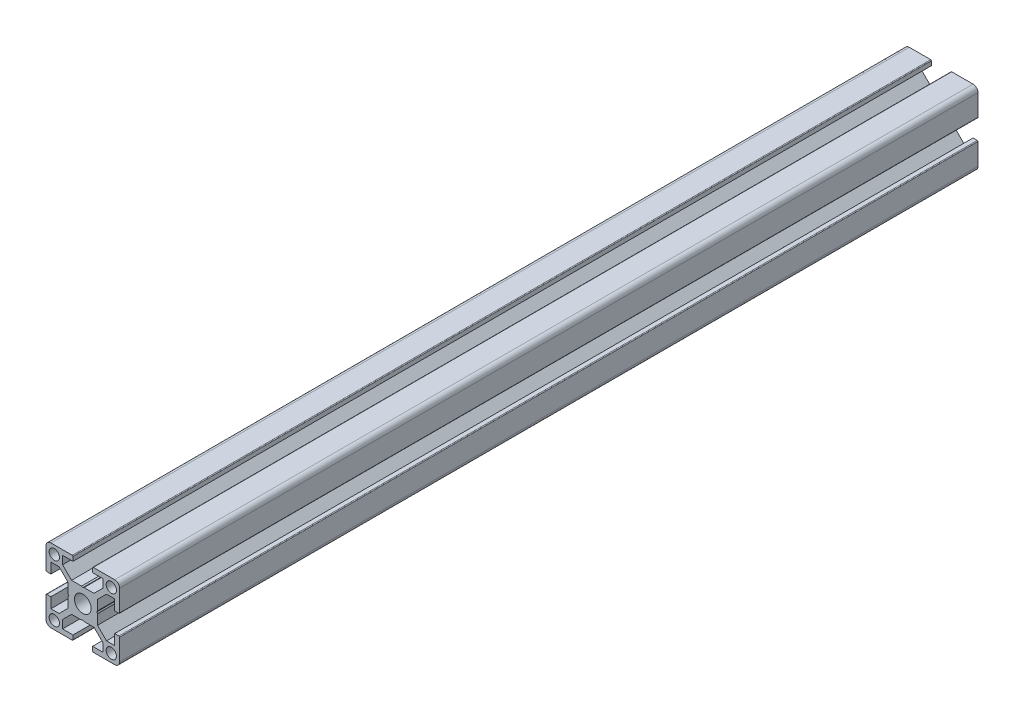
SolidWorks part; units mm, degrees
ref_plane "Front Plane" through (0, 0, 0) normal (0, 0, 1) x (1, 0, 0)
ref_plane "Top Plane" through (0, 0, 0) normal (0, 1, 0) x (1, 0, 0)
ref_plane "Right Plane" through (0, 0, 0) normal (1, 0, 0) x (0, 0, -1)
sketch "Sketch1" plane through (0, 0, 0) normal (0, 0, 1) x (1, 0, 0)
  line L0 (-14.7, 4) -> (-13, 4)
  line L1 (-13, 4) -> (-13, 8.25)
  line L2 (-13, 8.25) -> (-9.6642, 8.25)
  line L3 (-9.6642, 8.25) -> (-6, 4.5858)
  line L4 (-6, 4.5858) -> (-6, 0.5196)
  line L5 (-6, 0.5196) -> (-5.7, 0)
  line L6 (-5.7, 0) -> (-6, -0.5196)
  line L7 (-6, -0.5196) -> (-6, -4.5858)
  line L8 (-6, -4.5858) -> (-9.6642, -8.25)
  line L9 (-9.6642, -8.25) -> (-13, -8.25)
  line L10 (-13, -8.25) -> (-13, -4)
  line L11 (-13, -4) -> (-14.7, -4)
  line L12 (-15, -4.3) -> (-15, -13)
  line L13 (-13, -15) -> (-4.3, -15)
  line L14 (-4, -14.7) -> (-4, -13)
  line L15 (-4, -13) -> (-8.25, -13)
  line L16 (-8.25, -13) -> (-8.25, -9.6642)
  line L17 (-8.25, -9.6642) -> (-4.5858, -6)
  line L18 (-4.5858, -6) -> (-0.5196, -6)
  line L19 (-0.5196, -6) -> (0, -5.7)
  line L20 (0, -5.7) -> (0.5196, -6)
  line L21 (0.5196, -6) -> (4.5858, -6)
  line L22 (4.5858, -6) -> (8.25, -9.6642)
  line L23 (8.25, -9.6642) -> (8.25, -13)
  line L24 (8.25, -13) -> (4, -13)
  line L25 (4, -13) -> (4, -14.7)
  line L26 (4.3, -15) -> (13, -15)
  line L27 (15, -13) -> (15, -4.3)
  line L28 (14.7, -4) -> (13, -4)
  line L29 (13, -4) -> (13, -8.25)
  line L30 (13, -8.25) -> (9.6642, -8.25)
  line L31 (9.6642, -8.25) -> (6, -4.5858)
  line L32 (6, -4.5858) -> (6, -0.5196)
  line L33 (6, -0.5196) -> (5.7, 0)
  line L34 (5.7, 0) -> (6, 0.5196)
  line L35 (6, 0.5196) -> (6, 4.5858)
  line L36 (6, 4.5858) -> (9.6642, 8.25)
  line L37 (9.6642, 8.25) -> (13, 8.25)
  line L38 (13, 8.25) -> (13, 4)
  line L39 (13, 4) -> (14.7, 4)
  line L40 (15, 4.3) -> (15, 13)
  line L41 (13, 15) -> (4.3, 15)
  line L42 (4, 14.7) -> (4, 13)
  line L43 (4, 13) -> (8.25, 13)
  line L44 (8.25, 13) -> (8.25, 9.6642)
  line L45 (8.25, 9.6642) -> (4.5858, 6)
  line L46 (4.5858, 6) -> (0.5196, 6)
  line L47 (0.5196, 6) -> (0, 5.7)
  line L48 (0, 5.7) -> (-0.5196, 6)
  line L49 (-0.5196, 6) -> (-4.5858, 6)
  line L50 (-4.5858, 6) -> (-8.25, 9.6642)
  line L51 (-8.25, 9.6642) -> (-8.25, 13)
  line L52 (-8.25, 13) -> (-4, 13)
  line L53 (-4, 13) -> (-4, 14.7)
  line L54 (-4.3, 15) -> (-13, 15)
  line L55 (-15, 13) -> (-15, 4.3)
  arc A0 (-15, 4.3) -> (-14.7, 4) centre (-14.7, 4.3) ccw
  arc A1 (-14.7, -4) -> (-15, -4.3) centre (-14.7, -4.3) ccw
  arc A2 (-15, -13) -> (-13, -15) centre (-13, -13) ccw
  arc A3 (-4.3, -15) -> (-4, -14.7) centre (-4.3, -14.7) ccw
  arc A4 (4, -14.7) -> (4.3, -15) centre (4.3, -14.7) ccw
  arc A5 (13, -15) -> (15, -13) centre (13, -13) ccw
  arc A6 (15, -4.3) -> (14.7, -4) centre (14.7, -4.3) ccw
  arc A7 (14.7, 4) -> (15, 4.3) centre (14.7, 4.3) ccw
  arc A8 (15, 13) -> (13, 15) centre (13, 13) ccw
  arc A9 (4.3, 15) -> (4, 14.7) centre (4.3, 14.7) ccw
  arc A10 (-4, 14.7) -> (-4.3, 15) centre (-4.3, 14.7) ccw
  arc A11 (-13, 15) -> (-15, 13) centre (-13, 13) ccw
  circle A12 centre (11.625, 11.625) radius 2.1
  circle A13 centre (11.625, -11.625) radius 2.1
  circle A14 centre (0, 0) radius 3.4
  circle A15 centre (-11.625, -11.625) radius 2.1
  circle A16 centre (-11.625, 11.625) radius 2.1
extrude "Boss-Extrude1" add sketch "Sketch1" along normal blind 350
